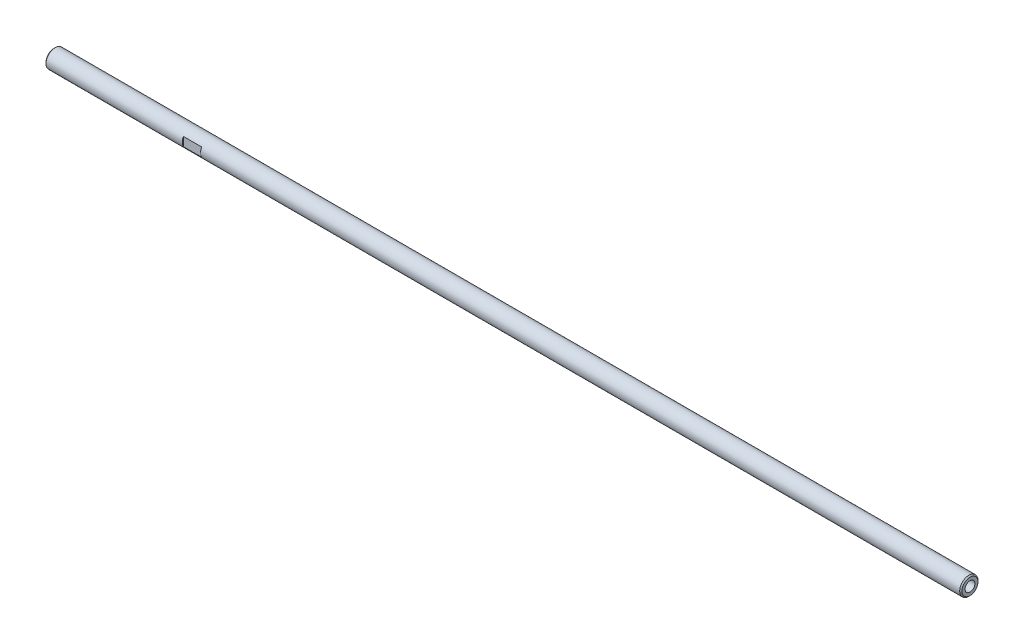
SolidWorks part; units mm, degrees
ref_plane "前视基准面" through (0, 0, 0) normal (0, 0, 1) x (1, 0, 0)
ref_plane "上视基准面" through (0, 0, 0) normal (0, 1, 0) x (1, 0, 0)
ref_plane "右视基准面" through (0, 0, 0) normal (1, 0, 0) x (0, 0, -1)
sketch "草图1" plane through (0, 0, 0) normal (0, 0, 1) x (1, 0, 0)
  line L0 (0, 0) -> (50000, 0) construction
  line L1 (0, 0) -> (0, 50000) construction
  line L2 (-190, 2.15) -> (-188.7081, 0)
  line L3 (-200, 4) -> (200, 4)
  line L4 (-200, 4) -> (-200, 0)
  line L5 (-200, 0) -> (200, 0)
  line L6 (200, 4) -> (200, 0)
  line L8 (-200, 0) -> (-200, 2.15)
  line L9 (-200, 2.15) -> (-190, 2.15)
  line L12 (200, 0) -> (200, 2.15)
  line L13 (200, 2.15) -> (190, 2.15)
  line L15 (190, 2.15) -> (188.7081, 0)
  dimension "D1" = 400
  dimension "D2" = 8
  dimension "D3" = 59
  dimension "D4" = 59
  dimension "D5" = 10
  dimension "D6" = 4.3
  dimension "D7" = 4.3
  dimension "D8" = 10
revolve "旋转1" add sketch "草图1" angle 360 about L0
cosmetic thread "装饰螺纹线1" parameters "D2"=5
cosmetic thread "装饰螺纹线2" parameters "D2"=5
ref_plane "基准面2" through (0, 4, 0) normal (0, 1, 0) x (1, 0, 0)
chamfer "倒角1" distance 0.5 angle 45 2 edges at (200, 0, 4) (-200, 0, 4)
ref_plane "基准面1" through (-140, 0, 0) normal (-1, 0, 0) x (0, 0, 1)
sketch "草图2" plane through (-140, 0, 0) normal (-1, 0, 0) x (0, 0, 1)
  line L1 (-3.5, -4) -> (3.5, -4)
  line L2 (-3.5, -4) -> (-3.5, 4)
  line L3 (-3.5, 4) -> (3.5, 4)
  line L4 (3.5, -4) -> (3.5, 4)
  line L5 (-3.5, -4) -> (3.5, 4) construction
  line L6 (-3.5, 4) -> (3.5, -4) construction
  circle A0 centre (0, 0) radius 4 construction
  point P0 (0, 0)
  dimension "D1" = 7
extrude "切除-拉伸1" cut sketch "草图2" against normal blind 8 flip side to cut
sketch "草图3" plane through (0, 0, 0) normal (0, 0, 1) x (1, 0, 0)
  line L0 (0, 0) -> (50000, 0) construction
  line L1 (-200, 3.5) -> (-200, -3.5) construction
  circle A0 centre (-180, 0) radius 1.5
  dimension "D1" = 3
  dimension "D2" = 20
extrude "切除-拉伸2" [suppressed] cut sketch "草图3" against normal up to next and the other way up to next
sketch "草图4" [suppressed] plane through (0, 6, 0) normal (0, 1, 0) x (1, 0, 0)
  line L0 (25, -5.5) -> (25, 5.5) construction
  line L1 (9, 6.5) -> (15, 6.5)
  line L2 (9, 6.5) -> (9, -6.5)
  line L3 (9, -6.5) -> (15, -6.5)
  line L4 (15, 6.5) -> (15, -6.5)
  line L5 (9, 6.5) -> (15, -6.5) construction
  line L6 (9, -6.5) -> (15, 6.5) construction
  point P0 (12, 0)
  dimension "D1" = 9
  dimension "D2" = 6
  dimension "D3" = 10
  dimension "D4" = 10
extrude "切除-拉伸3" [suppressed] cut sketch "草图4" against normal blind 1
sketch "草图5" [suppressed] plane through (0, 6, 0) normal (0, 1, 0) x (1, 0, 0)
  line L0 (25, -5.5) -> (25, 5.5) construction
  line L1 (-21, 6.5) -> (-15, 6.5)
  line L2 (-21, 6.5) -> (-21, -6.5)
  line L3 (-21, -6.5) -> (-15, -6.5)
  line L4 (-15, 6.5) -> (-15, -6.5)
  line L5 (-21, 6.5) -> (-15, -6.5) construction
  line L6 (-21, -6.5) -> (-15, 6.5) construction
  line L7 (9, 6.5) -> (15, 6.5)
  line L8 (9, 6.5) -> (9, -6.5)
  line L9 (9, -6.5) -> (15, -6.5)
  line L10 (15, 6.5) -> (15, -6.5)
  line L11 (9, 6.5) -> (15, -6.5) construction
  line L12 (9, -6.5) -> (15, 6.5) construction
  line L13 (-25, 5.5) -> (-25, -5.5) construction
  point P0 (-18, 0)
  point P5 (12, 0)
  dimension "D1" = 9
  dimension "D2" = 9
  dimension "D3" = 10
  dimension "D4" = 6
  dimension "D5" = 6
  dimension "D6" = 4
extrude "切除-拉伸4" [suppressed] cut sketch "草图5" against normal blind 1
